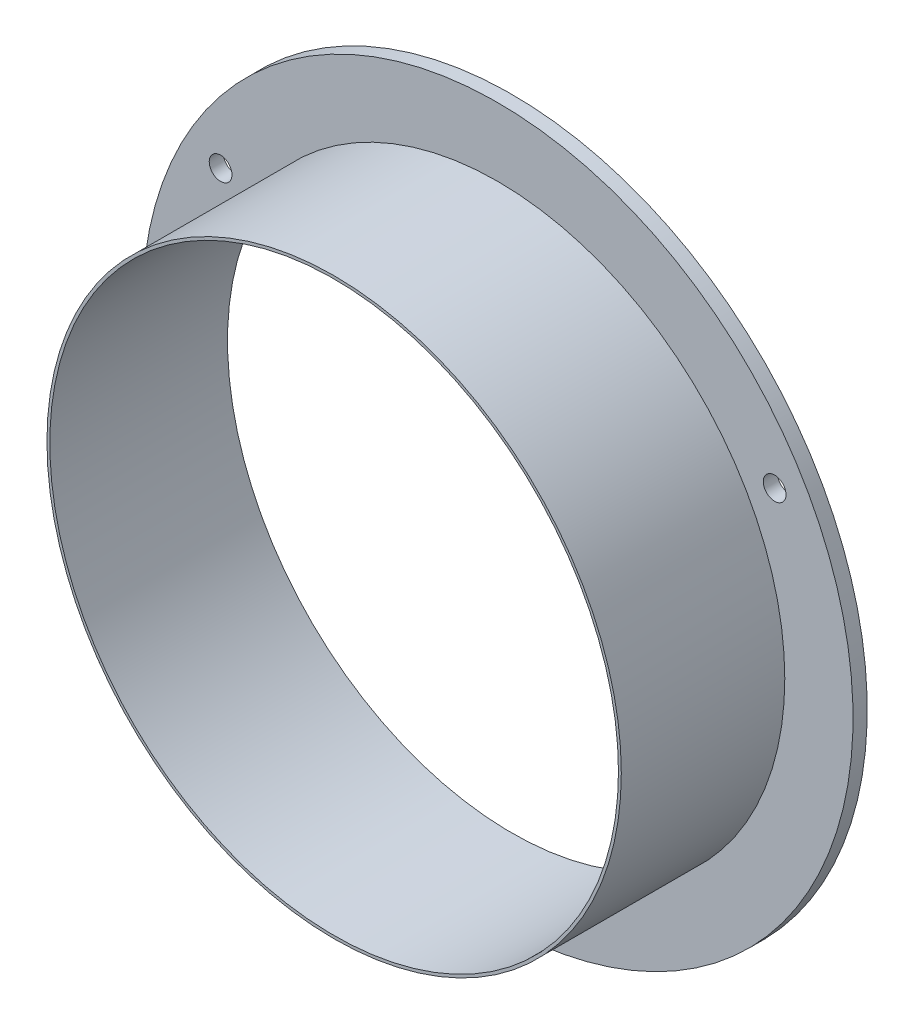
SolidWorks part; units mm, degrees
ref_plane "Plan de face" through (0, 0, 0) normal (0, 0, 1) x (1, 0, 0)
ref_plane "Plan de dessus" through (0, 0, 0) normal (0, 1, 0) x (1, 0, 0)
ref_plane "Plan de droite" through (0, 0, 0) normal (1, 0, 0) x (0, 0, -1)
sketch "Esquisse1" plane through (0, 0, 0) normal (0, 0, 1) x (1, 0, 0)
  circle A0 centre (0, 0) radius 40
  circle A1 centre (0, 0) radius 40.4
  dimension "D1" = 80
  dimension "D2" = 0.4
extrude "Boss.-Extru.1" add sketch "Esquisse1" against normal blind 25
sketch "Esquisse2" plane through (0, 0, -25) normal (0, 0, -1) x (-1, 0, 0)
  line L1 (-38.9711, 22.5) -> (0, -45) construction
  line L2 (0, -45) -> (38.9711, 22.5) construction
  line L3 (38.9711, 22.5) -> (-38.9711, 22.5) construction
  circle A0 centre (0, 0) radius 45 construction
  circle A1 centre (-38.9711, 22.5) radius 1.6
  circle A2 centre (38.9711, 22.5) radius 1.6
  circle A3 centre (0, -45) radius 1.6
  circle A4 centre (0, 0) radius 50
  circle A5 centre (0, 0) radius 40 construction
  circle A6 centre (0, 0) radius 40
  dimension "D1" = 90
  dimension "D2" = 3.2
  dimension "D3" = 3.2
  dimension "D4" = 3.2
  dimension "D5" = 100
extrude "Boss.-Extru.2" add sketch "Esquisse2" against normal blind 2
